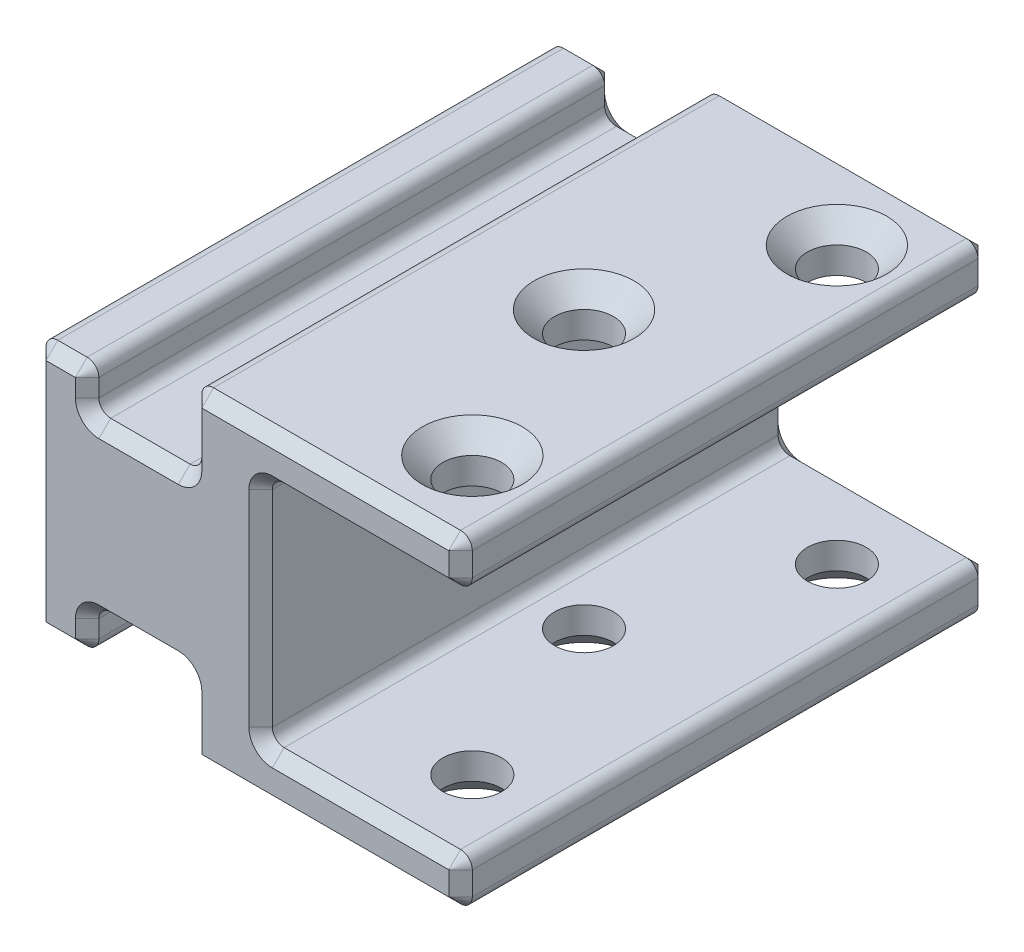
SolidWorks part; units mm, degrees
ref_plane "Front" through (0, 0, 0) normal (0, 0, 1) x (1, 0, 0)
ref_plane "Top" through (0, 0, 0) normal (0, 1, 0) x (1, 0, 0)
ref_plane "Right" through (0, 0, 0) normal (1, 0, 0) x (0, 0, -1)
sketch "Sketch1" plane through (0, 0, 0) normal (0, 0, 1) x (1, 0, 0)
  line L0 (0, -10.625) -> (0, 10.625)
  line L1 (0, 10.625) -> (4.5, 10.625)
  line L2 (4.5, 10.625) -> (4.5, 7.125)
  line L3 (4.5, 7.125) -> (13.25, 7.125)
  line L4 (13.25, 7.125) -> (13.25, 13.75)
  line L5 (13.25, 13.75) -> (36.25, 13.75)
  line L6 (36.25, 13.75) -> (36.25, 9.75)
  line L7 (36.25, 9.75) -> (19.25, 9.75)
  line L8 (19.25, 9.75) -> (19.25, -9.75)
  line L9 (0, 0) -> (52.8183, 0) construction
  line L10 (36.25, -9.75) -> (19.25, -9.75)
  line L11 (36.25, -13.75) -> (36.25, -9.75)
  line L12 (13.25, -13.75) -> (36.25, -13.75)
  line L13 (13.25, -7.125) -> (13.25, -13.75)
  line L14 (4.5, -7.125) -> (13.25, -7.125)
  line L15 (4.5, -10.625) -> (4.5, -7.125)
  line L16 (0, -10.625) -> (4.5, -10.625)
  point P13 (19.25, 0)
  dimension "D1" = 21.25
  dimension "D2" = 4.5
  dimension "D3" = 8.75
  dimension "D4" = 19.5
  dimension "D5" = 4
  dimension "D6" = 17
  dimension "D7" = 6
  dimension "D8" = 14.25
extrude "Boss-Extrude1" add sketch "Sketch1" along normal mid plane 45
sketch "Sketch2" plane through (0, -13.75, 0) normal (0, -1, 0) x (1, 0, 0)
  line L0 (0, 0) -> (47.8821, 0) construction
  line L1 (13.25, 22.5) -> (36.25, 22.5) construction
  line L2 (36.25, 22.5) -> (36.25, -22.5) construction
  circle A0 centre (30.25, 15.5) radius 2.5
  circle A1 centre (24.25, 0) radius 2.5
  circle A2 centre (30.25, -15.5) radius 2.5
  dimension "D1" = 7
  dimension "D4" = 5
  dimension "D2" = 6
  dimension "D3" = 6
extrude "Cut-Extrude1" cut sketch "Sketch2" against normal through all
chamfer "Chamfer1" distance 1.75 angle 45 6 edges at (30.25, 13.75, -18) (24.25, 13.75, -2.5) (30.25, 13.75, 13) (30.25, -13.75, -18) (30.25, -13.75, 13) (24.25, -13.75, -2.5)
fillet "Fillet1" radius 1 16 edges at (4.5, 10.625, 0) (4.5, 7.125, 0) (13.25, 7.125, 0) (13.25, 13.75, 0) (36.25, 13.75, 0) (36.25, 9.75, 0) (19.25, 9.75, 0) (19.25, -9.75, 0) (36.25, -9.75, 0) (36.25, -13.75, 0) (13.25, -13.75, 0) (13.25, -7.125, 0) (4.5, -7.125, 0) (0, -10.625, 0) (0, 10.625, 0) (4.5, -10.625, 0)
chamfer "Chamfer2" distance 1 angle 45 64 edges at (24.75, 13.75, -22.5) (13.5429, 13.4571, -22.5) (35.9571, 13.4571, -22.5) (13.25, 10.4375, -22.5) (36.25, 11.75, -22.5) (12.9571, 7.4179, -22.5) (35.9571, 10.0429, -22.5) (8.875, 7.125, -22.5) (27.75, 9.75, -22.5) (4.7929, 7.4179, -22.5) (19.5429, 9.4571, -22.5) (4.5, 8.875, -22.5) (19.25, 0, -22.5) (4.2071, 10.3321, -22.5) (19.5429, -9.4571, -22.5) (2.25, 10.625, -22.5) (27.75, -9.75, -22.5) (0.2929, 10.3321, -22.5) (35.9571, -10.0429, -22.5) (0, 0, -22.5) (36.25, -11.75, -22.5) (0.2929, -10.3321, -22.5) (35.9571, -13.4571, -22.5) (2.25, -10.625, -22.5) (24.75, -13.75, -22.5) (4.2071, -10.3321, -22.5) (13.5429, -13.4571, -22.5) (4.5, -8.875, -22.5) (13.25, -10.4375, -22.5) (4.7929, -7.4179, -22.5) (12.9571, -7.4179, -22.5) (8.875, -7.125, -22.5) (24.75, 13.75, 22.5) (13.5429, 13.4571, 22.5) (35.9571, 13.4571, 22.5) (13.25, 10.4375, 22.5) (36.25, 11.75, 22.5) (12.9571, 7.4179, 22.5) (35.9571, 10.0429, 22.5) (8.875, 7.125, 22.5) (27.75, 9.75, 22.5) (4.7929, 7.4179, 22.5) (19.5429, 9.4571, 22.5) (4.5, 8.875, 22.5) (19.25, 0, 22.5) (4.2071, 10.3321, 22.5) (19.5429, -9.4571, 22.5) (2.25, 10.625, 22.5) (27.75, -9.75, 22.5) (0.2929, 10.3321, 22.5) (35.9571, -10.0429, 22.5) (0, 0, 22.5) (36.25, -11.75, 22.5) (0.2929, -10.3321, 22.5) (35.9571, -13.4571, 22.5) (2.25, -10.625, 22.5) (24.75, -13.75, 22.5) (4.2071, -10.3321, 22.5) (13.5429, -13.4571, 22.5) (4.5, -8.875, 22.5) (13.25, -10.4375, 22.5) (4.7929, -7.4179, 22.5) (12.9571, -7.4179, 22.5) (8.875, -7.125, 22.5)
